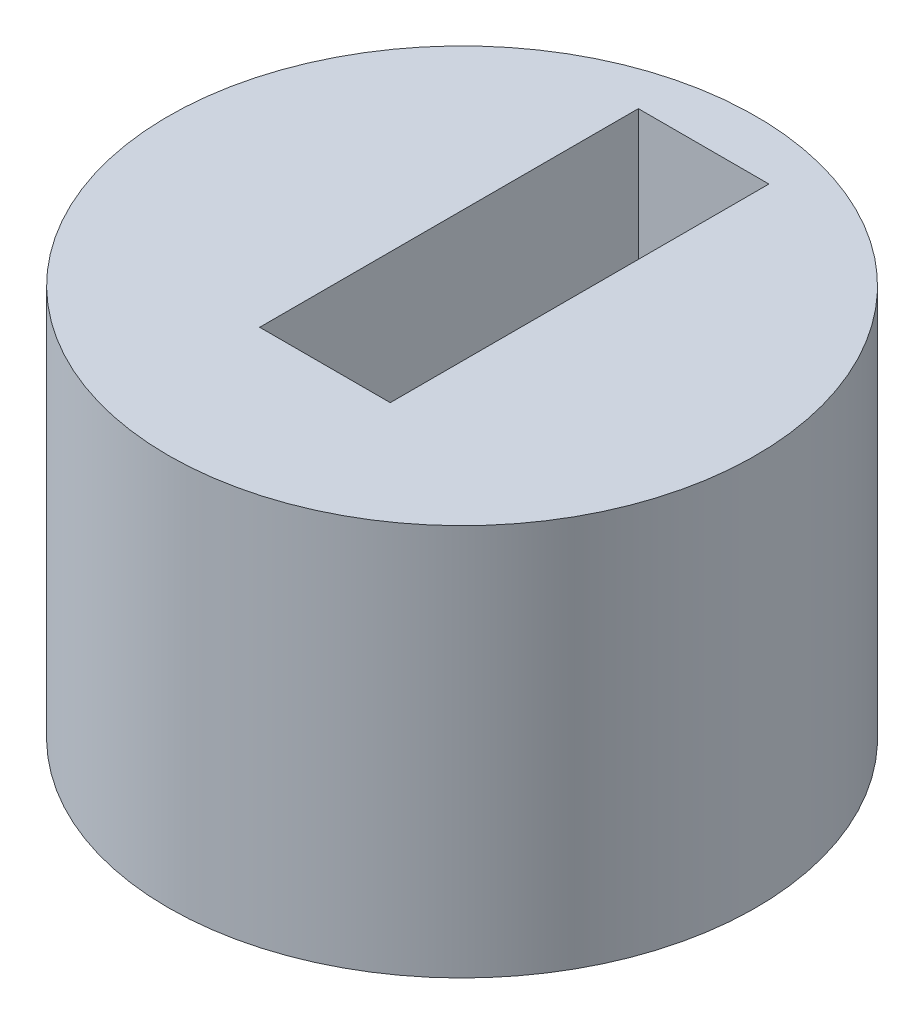
SolidWorks part; units mm, degrees
ref_plane "Front Plane" through (0, 0, 0) normal (0, 0, 1) x (1, 0, 0)
ref_plane "Top Plane" through (0, 0, 0) normal (0, 1, 0) x (1, 0, 0)
ref_plane "Right Plane" through (0, 0, 0) normal (1, 0, 0) x (0, 0, -1)
sketch "Sketch1" plane through (0, 0, 0) normal (0, 1, 0) x (1, 0, 0)
  circle A0 centre (0, 0) radius 45
  dimension "D1" = 90
extrude "Boss-Extrude1" add sketch "Sketch1" along normal blind 60
sketch "Sketch2" plane through (0, 60, 0) normal (0, 1, 0) x (1, 0, 0)
  line L1 (10, -21) -> (-10, -21)
  line L2 (10, -21) -> (10, 37)
  line L3 (10, 37) -> (-10, 37)
  line L4 (-10, -21) -> (-10, 37)
  line L5 (10, -21) -> (-10, 37) construction
  line L6 (10, 37) -> (-10, -21) construction
  point P0 (0, 0)
  point P6 (0, 0)
  dimension "D1" = 20
  dimension "D2" = 58
  dimension "D3" = 37
extrude "Cut-Extrude1" cut sketch "Sketch2" against normal blind 40
